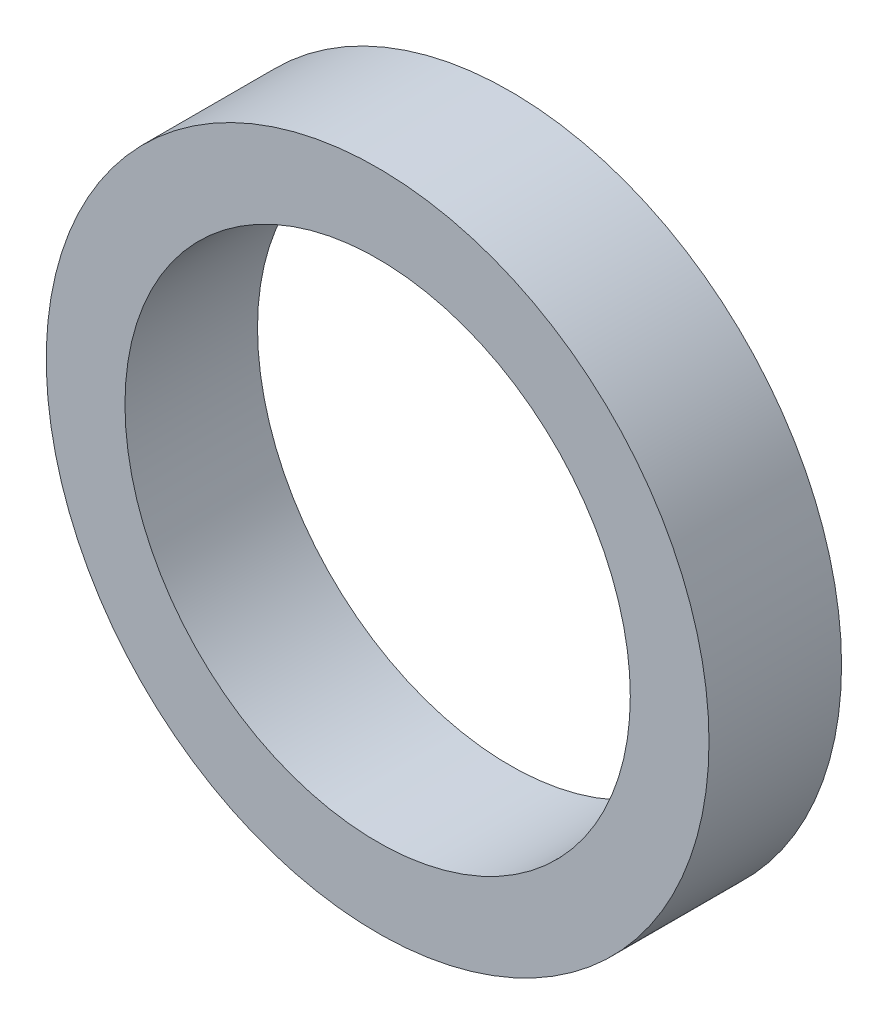
SolidWorks part; units mm, degrees
material "AISI 4340 Steel, normalized"
ref_plane "Front Plane" through (0, 0, 0) normal (0, 0, 1) x (1, 0, 0)
ref_plane "Top Plane" through (0, 0, 0) normal (0, 1, 0) x (1, 0, 0)
ref_plane "Right Plane" through (0, 0, 0) normal (1, 0, 0) x (0, 0, -1)
sketch "Sketch1" plane through (0, 0, 0) normal (0, 0, 1) x (1, 0, 0)
  circle A0 centre (0, 0) radius 2
  circle A1 centre (0, 0) radius 1.525
extrude "Inner_Race_Spacer_H0p8" add sketch "Sketch1" along normal blind 0.8 from offset 1
